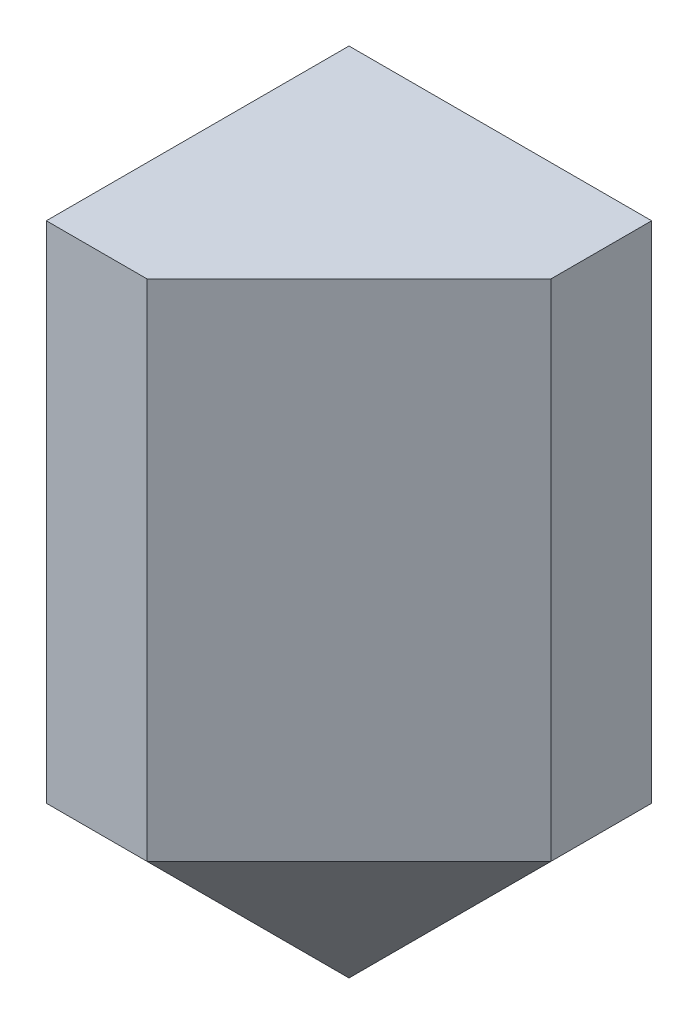
SolidWorks part; units mm, degrees
material "ABS"
ref_plane "Piano frontale" through (0, 0, 0) normal (0, 0, 1) x (1, 0, 0)
ref_plane "Piano superiore" through (0, 0, 0) normal (0, 1, 0) x (1, 0, 0)
ref_plane "Piano destro" through (0, 0, 0) normal (1, 0, 0) x (0, 0, -1)
sketch "Schizzo1" plane through (0, 0, 0) normal (0, 0, 1) x (1, 0, 0)
  line L1 (0, 0) -> (30, 0)
  line L2 (0, 0) -> (0, 40)
  line L3 (0, 40) -> (30, 40)
  line L4 (30, 0) -> (30, 40)
  dimension "D1" = 30
  dimension "D2" = 40
extrude "Estrusione-Estrusione1" add sketch "Schizzo1" along normal blind 30
chamfer "Smusso1" distance 20 angle 45 3 edges at (30, 20, 30) (30, 0, 15) (15, 0, 30)
sketch "Schizzo2" plane through (0, 40, 0) normal (0, 1, 0) x (1, 0, 0)
  line L0 (0, 0) -> (30, 0)
  line L1 (30, 0) -> (30, -10)
  line L2 (30, -10) -> (10, -30)
  line L3 (10, -30) -> (0, -30)
  line L4 (0, -30) -> (0, 0)
extrude "Estrusione-Estrusione2" add sketch "Schizzo2" along normal blind 30
hole_wizard "Foro per Vite M5-1" positions "Schizzo3" profile "Schizzo4" hole size "M5" standard "ISO"
sketch "Schizzo3" plane through (0, 0, 0) normal (-1, 0, 0) x (0, 0, 1)
  line L4 (0, 70) -> (30, 70) construction
  line L5 (0, 70) -> (0, 0) construction
  point P0 (18, 20)
  dimension "D1" = 18
  dimension "D2" = 50
sketch "Schizzo4" plane through (0, 20, 18) normal (0, 1, 0) x (0, 0, 1)
  line L0 (0, 0) -> (0, 14.6524)
  line L1 (0, 14.6524) -> (2.75, 13)
  line L2 (2.75, 13) -> (2.75, 0)
  line L5 (2.75, 0) -> (0, 0)
  line L10 (0, 14.6524) -> (-2.75, 13) construction
  line L11 (0, -6.35) -> (0, 107.95) construction
  dimension "Hole Dia." = 5.5
  dimension "Hole Depth" = 13
  dimension "Drill Angle" = 118
hole_wizard "Foro per Vite M5-2" positions "Schizzo3D1" profile "Schizzo5" hole size "M5" standard "ISO"
sketch3d "Schizzo3D1"
  line L0 (14, 20, 0) -> (14, 34, 0) construction
  line L2 (0, 70, 0) -> (0, 0, 0) construction
  line L4 (14, 48, 0) -> (14, 34, 0) construction
  line L5 (30, 70, 0) -> (0, 70, 0) construction
  line L6 (14, 20, 0) -> (18, 20, 0) construction
  point P21 (14, 48, 0)
  point P37 (18, 20, 0)
  point P40 (20.4554, 20, 0)
  dimension "D1" = 14
  dimension "D2" = 14
  dimension "D3" = 22
  dimension "D5" = 4
  dimension "D4" = 14
sketch "Schizzo5" plane through (18, 20, 0) normal (1, 0, 0) x (0, 1, 0)
  line L0 (0, 0) -> (0, 14.6524)
  line L1 (0, 14.6524) -> (2.75, 13)
  line L2 (2.75, 13) -> (2.75, 0)
  line L5 (2.75, 0) -> (0, 0)
  line L10 (0, 14.6524) -> (-2.75, 13) construction
  line L11 (0, -6.35) -> (0, 107.95) construction
  dimension "Hole Dia." = 5.5
  dimension "Hole Depth" = 13
  dimension "Drill Angle" = 118
sketch "Schizzo6" plane through (0, 0, 0) normal (-1, 0, 0) x (0, 0, 1)
  line L0 (0, 70) -> (30, 70) construction
  line L1 (30, 70) -> (30, 20) construction
  circle A0 centre (15, 55) radius 7.5
  dimension "D1" = 15
  dimension "D2" = 15
  dimension "D3" = 15
extrude "Taglio-Estrusione1" cut sketch "Schizzo6" against normal blind 3
sketch "Schizzo7" plane through (3, 0, 0) normal (-1, 0, 0) x (0, 0, 1)
  point P0 (15, 55)
hole_wizard "Foro per Vite M4-1" positions "Schizzo7" profile "Schizzo8" hole size "M4" standard "ISO"
sketch "Schizzo8" plane through (3, 55, 15) normal (0, 1, 0) x (0, 0, 1)
  line L0 (0, 0) -> (0, 11.3219)
  line L1 (0, 11.3219) -> (2.2, 10)
  line L2 (2.2, 10) -> (2.2, 0)
  line L5 (2.2, 0) -> (0, 0)
  line L10 (0, 11.3219) -> (-2.2, 10) construction
  line L11 (0, -6.35) -> (0, 107.95) construction
  dimension "Hole Dia." = 4.4
  dimension "Hole Depth" = 10
  dimension "Drill Angle" = 118
